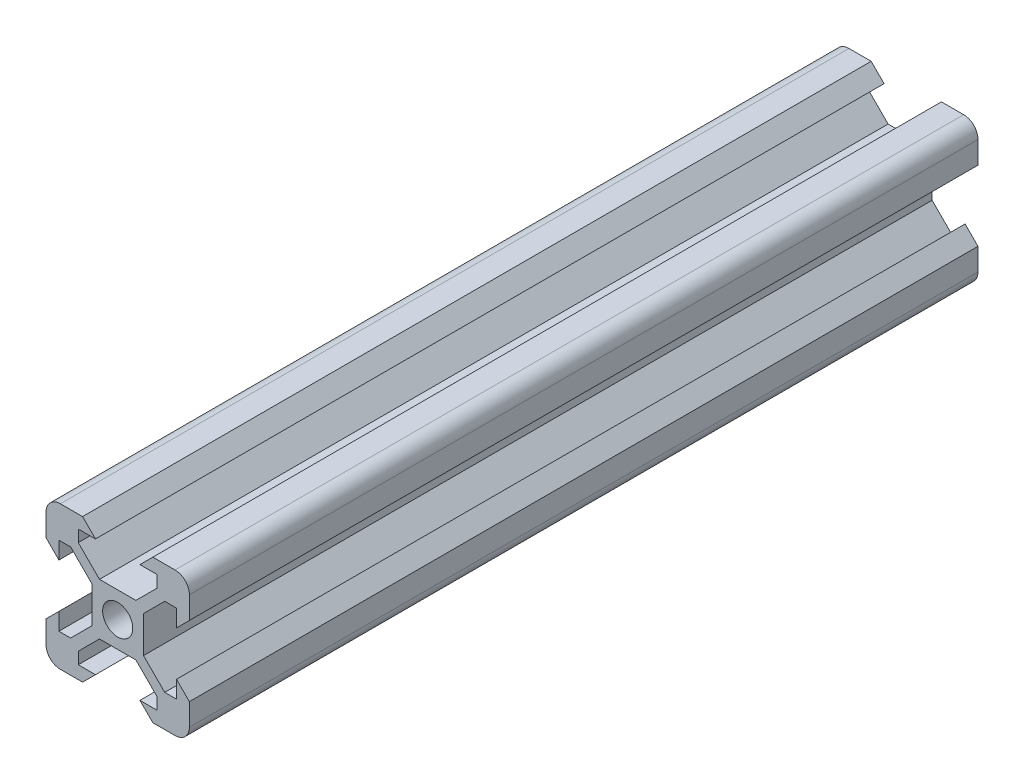
SolidWorks part; units mm, degrees
material "6061 Alloy"
ref_plane "Front Plane" through (0, 0, 0) normal (0, 0, 1) x (1, 0, 0)
ref_plane "Top Plane" through (0, 0, 0) normal (0, 1, 0) x (1, 0, 0)
ref_plane "Right Plane" through (0, 0, 0) normal (1, 0, 0) x (0, 0, -1)
sketch "Sketch1" plane through (0, 0, 0) normal (0, 0, 1) x (1, 0, 0)
  line L0 (-4.9, -10) -> (-5.5, -10)
  line L1 (-10, -10) -> (10, -10) construction
  line L2 (-10, -10) -> (-10, 10) construction
  line L3 (-10, 10) -> (10, 10) construction
  line L4 (10, -10) -> (10, 10) construction
  line L5 (-10, -10) -> (10, 10) construction
  line L6 (-10, 10) -> (10, -10) construction
  line L7 (-3.6, 3.6) -> (3.6, 3.6)
  line L8 (-3.6, 3.6) -> (-3.6, -3.6)
  line L9 (-3.6, -3.6) -> (3.6, -3.6)
  line L10 (3.6, 3.6) -> (3.6, -3.6)
  line L11 (-8, 10) -> (-5.5, 10)
  line L12 (-10, 8) -> (-10, 5.5)
  line L13 (-10, 5.5) -> (-5.5, 5.5)
  line L14 (-5.5, 10) -> (-5.5, 5.5)
  line L15 (8, 10) -> (5.5, 10)
  line L16 (10, 8) -> (10, 5.5)
  line L17 (10, 5.5) -> (5.5, 5.5)
  line L18 (5.5, 10) -> (5.5, 5.5)
  line L19 (8, -10) -> (5.5, -10)
  line L20 (10, -8) -> (10, -5.5)
  line L21 (10, -5.5) -> (5.5, -5.5)
  line L22 (5.5, -10) -> (5.5, -5.5)
  line L23 (-8, -10) -> (-5.5, -10)
  line L24 (-10, -8) -> (-10, -5.5)
  line L25 (-10, -5.5) -> (-5.5, -5.5)
  line L26 (-5.5, -10) -> (-5.5, -5.5)
  line L27 (-3.1, -8.2) -> (-4.9, -10)
  line L28 (-3.1, -8.2) -> (-5.5, -8.2)
  line L29 (4.9, -10) -> (5.5, -10)
  line L30 (3.1, -8.2) -> (4.9, -10)
  line L31 (3.1, -8.2) -> (5.5, -8.2)
  line L32 (-4.9, 10) -> (-5.5, 10)
  line L33 (-3.1, 8.2) -> (-4.9, 10)
  line L34 (-3.1, 8.2) -> (-5.5, 8.2)
  line L35 (4.9, 10) -> (5.5, 10)
  line L36 (0, 0) -> (17.4618, 0) construction
  line L37 (3.1, 8.2) -> (4.9, 10)
  line L38 (3.1, 8.2) -> (5.5, 8.2)
  line L39 (8.2, 3.1) -> (8.2, 5.5)
  line L40 (8.2, 3.1) -> (10, 4.9)
  line L41 (10, 4.9) -> (10, 5.5)
  line L42 (10, -4.9) -> (10, -5.5)
  line L43 (8.2, -3.1) -> (10, -4.9)
  line L44 (8.2, -3.1) -> (8.2, -5.5)
  line L57 (-8.2, -3.1) -> (-10, -4.9)
  line L58 (-10, -4.9) -> (-10, -5.5)
  line L61 (-8.2, -3.1) -> (-8.2, -5.5)
  line L62 (-8.2, 3.1) -> (-10, 4.9)
  line L63 (-10, 4.9) -> (-10, 5.5)
  line L66 (-8.2, 3.1) -> (-8.2, 5.5)
  line L67 (-2.7729, 2.7729) -> (-6.4508, 6.4508) construction
  line L68 (-2.2426, 3.3033) -> (-5.9205, 6.9812)
  line L69 (-3.3033, 2.2426) -> (-6.9812, 5.9205)
  line L70 (6.7372, 6.7372) -> (2.7729, 2.7729)
  line L71 (6.309, -6.309) -> (2.7729, -2.7729)
  line L72 (-2.8687, -2.8687) -> (-6.5971, -6.5971)
  line L73 (6.2069, 7.2675) -> (2.2426, 3.3033)
  line L74 (6.8393, -5.7786) -> (3.3033, -2.2426)
  line L75 (-3.399, -2.3384) -> (-7.1274, -6.0667)
  line L76 (7.2675, 6.2069) -> (3.3033, 2.2426)
  line L77 (5.7786, -6.8393) -> (2.2426, -3.3033)
  line L78 (-2.3384, -3.399) -> (-6.0667, -7.1274)
  circle A0 centre (0, 0) radius 2.1
  arc A1 (-8, -10) -> (-10, -8) centre (-8, -8) cw
  arc A2 (8, -10) -> (10, -8) centre (8, -8) ccw
  arc A3 (8, 10) -> (10, 8) centre (8, 8) cw
  arc A4 (-8, 10) -> (-10, 8) centre (-8, 8) ccw
  point P0 (0, 0)
  dimension "D3" = 4.2
  dimension "D12" = 2
  dimension "D1" = 20
  dimension "D4" = 6.4
  dimension "D5" = 6.4
  dimension "D6" = 6.4
  dimension "D7" = 6.4
  dimension "D8" = 4.5
  dimension "D9" = 4.5
  dimension "D10" = 4.5
  dimension "D11" = 4.5
  dimension "D13" = 45
  dimension "D19" = 45
  dimension "D20" = 6.2
  dimension "D23" = 1.8
  dimension "D24" = 1.8
  dimension "D28" = 0.75
  dimension "D26" = 0.75
  dimension "D27" = 0.75
  dimension "D29" = 0.75
extrude "Boss-Extrude1" add sketch "Sketch1" along normal blind 110
